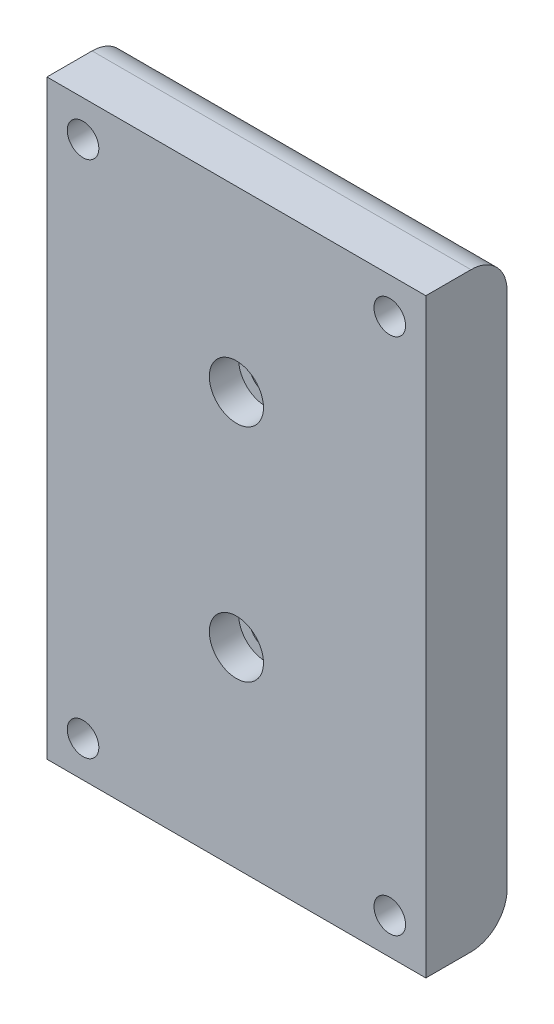
SolidWorks part; units mm, degrees
ref_plane "Front Plane" through (0, 0, 0) normal (0, 0, 1) x (1, 0, 0)
ref_plane "Top Plane" through (0, 0, 0) normal (0, 1, 0) x (1, 0, 0)
ref_plane "Right Plane" through (0, 0, 0) normal (1, 0, 0) x (0, 0, -1)
sketch "Sketch1" plane through (0, 0, 0) normal (0, 0, 1) x (1, 0, 0)
  line L1 (0, 0) -> (42, 0)
  line L2 (0, 0) -> (0, 65.5)
  line L3 (0, 65.5) -> (42, 65.5)
  line L4 (42, 0) -> (42, 65.5)
  dimension "D1" = 42
  dimension "D2" = 65.5
extrude "Boss-Extrude1" add sketch "Sketch1" along normal blind 9
sketch "Sketch2" plane through (0, 0, 0) normal (0, 0, -1) x (-1, 0, 0)
  line L0 (-42, 32.75) -> (0, 32.75) construction
  line L1 (-42, 0) -> (-42, 65.5) construction
  line L2 (0, 65.5) -> (0, 0) construction
  line L3 (-42, 45.75) -> (0, 45.75) construction
  line L4 (-21, 45.75) -> (-21, 21.25) construction
  line L5 (-25.5, 21.25) -> (-25.5, 35.0846)
  line L6 (-16.5, 21.25) -> (-16.5, 35.0846)
  arc A0 (-14.5556, 41.0098) -> (-27.4444, 41.0098) centre (-21, 45.75) ccw
  arc A1 (-25.5, 21.25) -> (-16.5, 21.25) centre (-21, 21.25) ccw
  arc A2 (-16.5, 35.0846) -> (-14.5556, 41.0098) centre (-6.5, 35.0846) cw
  arc A3 (-25.5, 35.0846) -> (-27.4444, 41.0098) centre (-35.5, 35.0846) ccw
  point P11 (-21, 45.75)
  dimension "D2" = 16
  dimension "D3" = 9
  dimension "D5" = 10
  dimension "D4" = 24.5
  dimension "D1" = 13
extrude "Cut-Extrude2" cut sketch "Sketch2" against normal blind 4.5
sketch "Sketch3" plane through (0, 0, 4.5) normal (0, 0, -1) x (-1, 0, 0)
  line L0 (-21, 45.75) -> (-21, 25.25) construction
  line L1 (-21, 25.25) -> (-21, 21.25) construction
  line L2 (-24, 21.25) -> (-24, 25.25)
  line L3 (-18, 25.25) -> (-18, 21.25)
  arc A0 (-18, 25.25) -> (-24, 25.25) centre (-21, 25.25) ccw
  arc A1 (-24, 21.25) -> (-18, 21.25) centre (-21, 21.25) ccw
  circle A2 centre (-21, 25.25) radius 1.75
  circle A3 centre (-21, 21.25) radius 1.75
  circle A4 centre (-21, 45.75) radius 1.75
  dimension "D2" = 6
  dimension "D4" = 3.5
  dimension "D5" = 3.5
  dimension "D1" = 20.5
  dimension "D3" = 4
extrude "Cut-Extrude5" cut sketch "Sketch3" against normal through all contours A3 | A4
sketch "Sketch5" plane through (0, 0, 9) normal (0, 0, 1) x (1, 0, 0)
  circle A0 centre (21, 21.25) radius 3
  circle A1 centre (21, 45.75) radius 3
  dimension "D1" = 6
extrude "Cut-Extrude6" cut sketch "Sketch5" against normal blind 3.25
fillet "Fillet1" radius 4 2 edges at (21, 0, 0) (21, 65.5, 0)
sketch "Sketch6" plane through (0, 0, 0) normal (0, 0, -1) x (-1, 0, 0)
  line L0 (-4, 61.5) -> (-4, 4) construction
  line L1 (-42, 65.5) -> (0, 65.5) construction
  line L2 (-42, 65.5) -> (-42, 0) construction
  line L3 (-42, 0) -> (0, 0) construction
  line L4 (0, 65.5) -> (0, 0) construction
  line L5 (-38, 4) -> (-4, 4) construction
  line L6 (-38, 61.5) -> (-38, 4) construction
  line L7 (-38, 61.5) -> (-4, 61.5) construction
  circle A0 centre (-38, 61.5) radius 1.75
  circle A1 centre (-4, 61.5) radius 1.75
  circle A2 centre (-4, 4) radius 1.75
  circle A3 centre (-38, 4) radius 1.75
  line M16 (-42, 4) -> (0, 4)
  dimension "D2" = 3.5
  dimension "D1" = 4
extrude "Cut-Extrude7" cut sketch "Sketch6" against normal through all contours A2 M16 | A2 M16 | A3 M16 | A3 M16 | A0 | A1
sketch "Sketch7" plane through (0, 0, 0) normal (0, 0, -1) x (-1, 0, 0)
  circle A0 centre (-38, 61.5) radius 3
  circle A1 centre (-4, 61.5) radius 3
  circle A2 centre (-4, 4) radius 3
  circle A3 centre (-38, 4) radius 3
  dimension "D1" = 6
extrude "Cut-Extrude8" cut sketch "Sketch7" against normal blind 3
